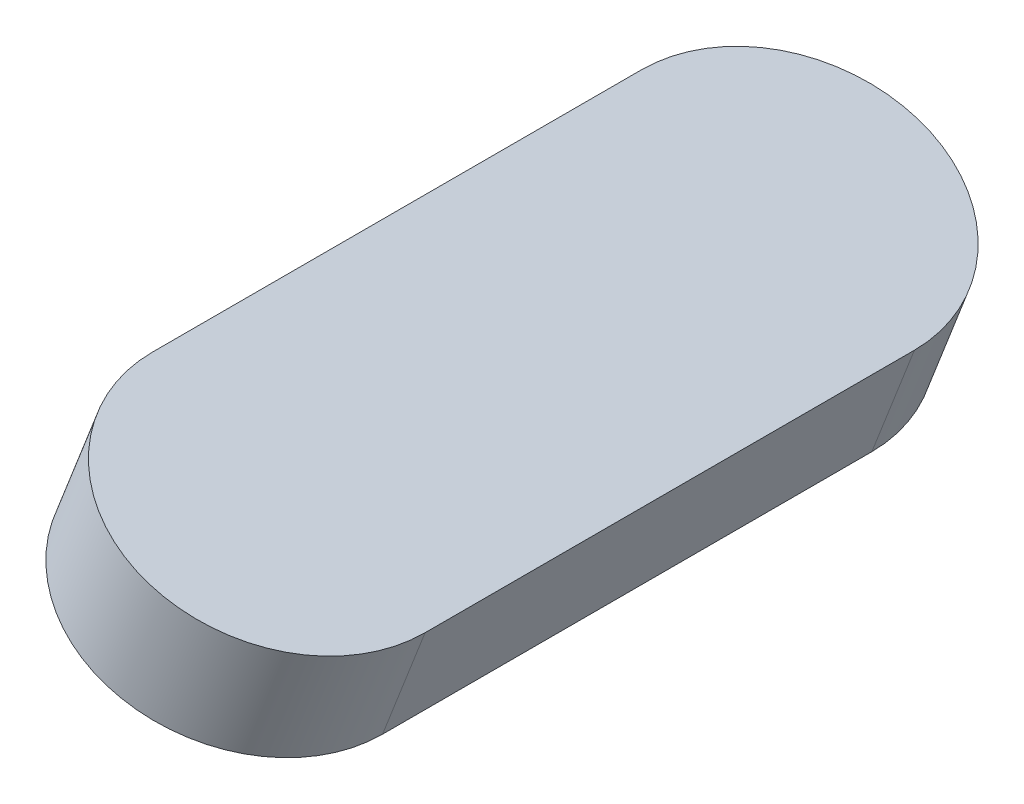
SolidWorks part; units mm, degrees
ref_plane "Front Plane" through (0, 0, 0) normal (0, 0, 1) x (1, 0, 0)
ref_plane "Top Plane" through (0, 0, 0) normal (0, 1, 0) x (1, 0, 0)
ref_plane "Right Plane" through (0, 0, 0) normal (1, 0, 0) x (0, 0, -1)
sketch "Sketch1" plane through (-4.899, -12.573, 0) normal (0.3631, 0.9318, 0) x (0.9318, -0.3631, 0)
  line L2 (1.8017, -37.3656) -> (1.8017, -26.7597)
  line L3 (-4.5483, -26.7597) -> (-4.5483, -37.3656)
  line L4 (1.8017, -37.3656) -> (1.8017, -26.7597)
  line L5 (-4.5483, -26.7597) -> (-4.5483, -37.3656)
  arc A2 (-4.5483, -37.3656) -> (1.8017, -37.3656) centre (-1.3733, -37.3656) ccw
  arc A3 (1.8017, -26.7597) -> (-4.5483, -26.7597) centre (-1.3733, -26.7597) ccw
  arc A4 (-4.5483, -37.3656) -> (1.8017, -37.3656) centre (-1.3733, -37.3656) ccw
  arc A5 (1.8017, -26.7597) -> (-4.5483, -26.7597) centre (-1.3733, -26.7597) ccw
  dimension "D1" = 0
extrude "Boss-Extrude1" add sketch "Sketch1" along normal blind 2.54
